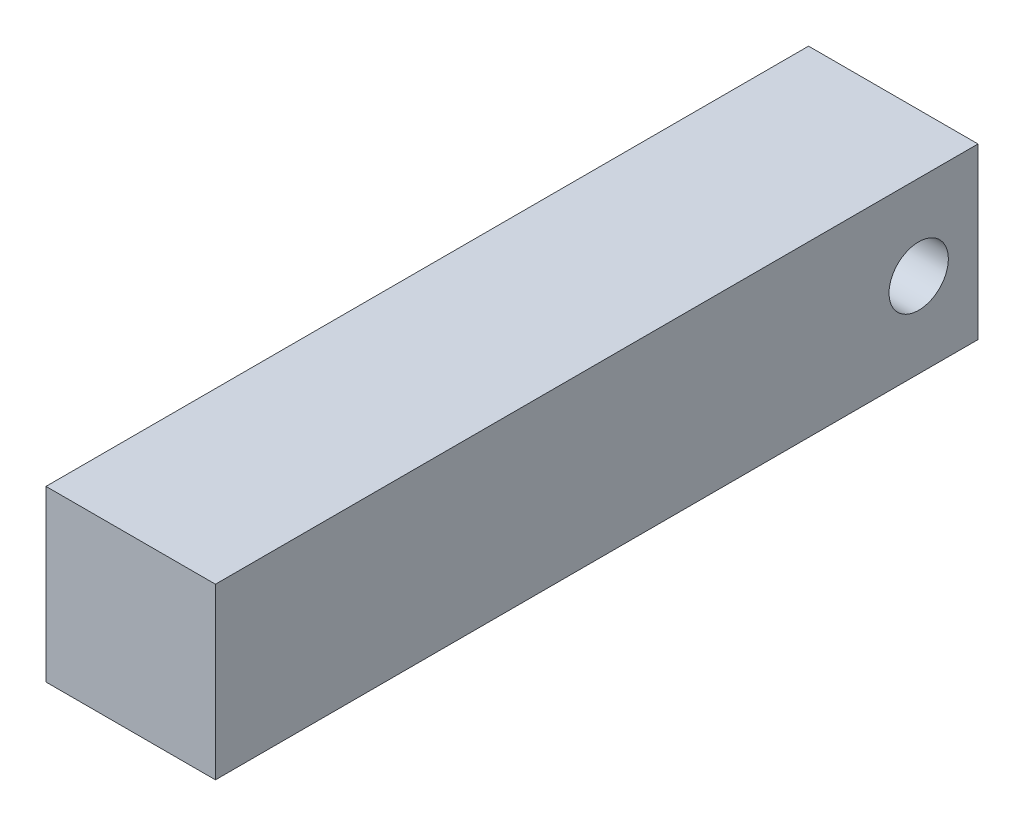
SolidWorks part; units mm, degrees
ref_plane "前视基准面" through (0, 0, 0) normal (0, 0, 1) x (1, 0, 0)
ref_plane "上视基准面" through (0, 0, 0) normal (0, 1, 0) x (1, 0, 0)
ref_plane "右视基准面" through (0, 0, 0) normal (1, 0, 0) x (0, 0, -1)
other "Configuration Table"
sketch "草图1" plane through (0, 0, 0) normal (0, 0, 1) x (1, 0, 0)
  line L1 (0, 0) -> (10, 0)
  line L2 (0, 0) -> (0, -10)
  line L3 (0, -10) -> (10, -10)
  line L4 (10, 0) -> (10, -10)
  dimension "D1" = 10
  dimension "D2" = 10
extrude "凸台-拉伸1" add sketch "草图1" along normal blind 45 contours L2 L3 L4 L1
sketch "草图2" plane through (0, 0, 0) normal (0, 0, -1) x (-1, 0, 0)
  line L0 (0, -10) -> (-10, -10) construction
  line L1 (-6.5, -2.5) -> (-3.5, -2.5)
  line L2 (-6.5, -2.5) -> (-6.5, -7.5)
  line L3 (-6.5, -7.5) -> (-3.5, -7.5)
  line L4 (-3.5, -2.5) -> (-3.5, -7.5)
  line L5 (-10, 0) -> (-10, -10) construction
  dimension "D1" = 3
  dimension "D2" = 5
  dimension "D3" = 2.5
  dimension "D4" = 3.5
extrude "切除-拉伸1" cut sketch "草图2" against normal blind 7
sketch "草图3" plane through (10, 0, 0) normal (1, 0, 0) x (0, 0, -1)
  line L0 (0, 0) -> (0, -10) construction
  line L1 (-45, 0) -> (0, 0) construction
  circle A0 centre (-3.5, -5) radius 1.75
  dimension "D1" = 3.5
  dimension "D2" = 3.5
  dimension "D3" = 5
extrude "切除-拉伸2" cut sketch "草图3" against normal up to next
